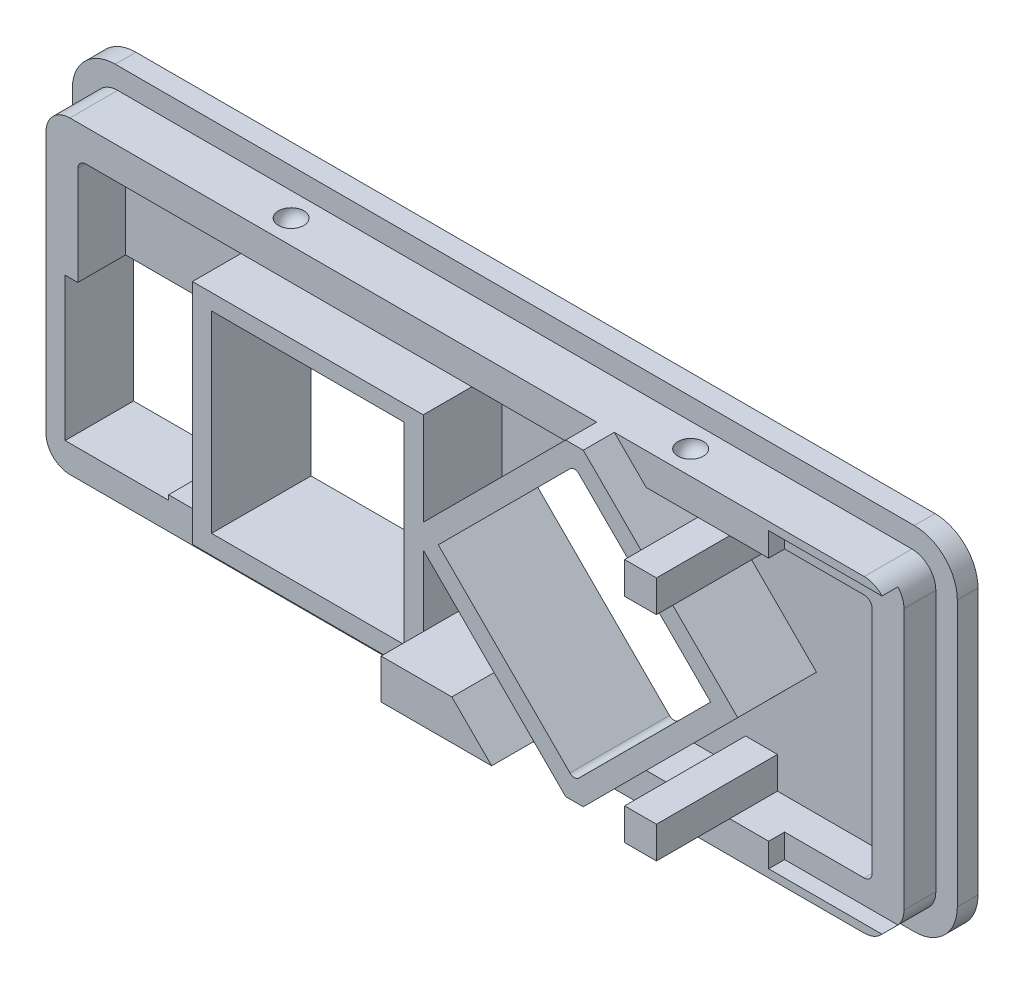
SolidWorks part; units mm, degrees
material "PLA"
ref_plane "Front Plane" through (0, 0, 0) normal (0, 0, 1) x (1, 0, 0)
ref_plane "Top Plane" through (0, 0, 0) normal (0, 1, 0) x (1, 0, 0)
ref_plane "Right Plane" through (0, 0, 0) normal (1, 0, 0) x (0, 0, -1)
sketch "Sketch1" plane through (0, 0, 0) normal (0, 0, 1) x (1, 0, 0)
  line L1 (2.7, 0) -> (52.9, 0)
  line L2 (0, 2.7) -> (0, 19.4)
  line L3 (2.7, 22.1) -> (52.9, 22.1)
  line L4 (55.6, 2.7) -> (55.6, 19.4)
  arc A0 (52.9, 0) -> (55.6, 2.7) centre (52.9, 2.7) ccw
  arc A1 (2.7, 0) -> (0, 2.7) centre (2.7, 2.7) cw
  arc A2 (0, 19.4) -> (2.7, 22.1) centre (2.7, 19.4) cw
  arc A3 (52.9, 22.1) -> (55.6, 19.4) centre (52.9, 19.4) cw
  point P9 (0, 0)
  dimension "D1" = 2.7
  dimension "D2" = 50.2
  dimension "D3" = 22.1
extrude "Boss-Extrude1" add sketch "Sketch1" along normal blind 1.3
sketch "Sketch4" plane through (0, 0, 1.3) normal (0, 0, 1) x (1, 0, 0)
  line L11 (54.25, 2.7) -> (54.25, 19.4)
  line L12 (52.9, 20.75) -> (2.7, 20.75)
  line L13 (1.35, 19.4) -> (1.35, 2.7)
  line L14 (2.7, 1.35) -> (52.9, 1.35)
  line L15 (54.25, 2.85) -> (54.25, 19.25)
  line L16 (52.75, 20.75) -> (2.85, 20.75)
  line L17 (1.35, 19.25) -> (1.35, 2.85)
  line L18 (2.85, 1.35) -> (52.75, 1.35)
  arc A4 (54.25, 19.25) -> (52.75, 20.75) centre (52.75, 19.25) ccw
  arc A5 (54.25, 2.85) -> (52.75, 1.35) centre (52.75, 2.85) cw
  arc A6 (1.35, 2.85) -> (2.85, 1.35) centre (2.85, 2.85) ccw
  arc A7 (2.85, 20.75) -> (1.35, 19.25) centre (2.85, 19.25) ccw
  arc A8 (52.9, 1.35) -> (54.25, 2.7) centre (52.9, 2.7) ccw
  arc A10 (54.25, 19.4) -> (52.9, 20.75) centre (52.9, 19.4) ccw
  arc A12 (2.7, 20.75) -> (1.35, 19.4) centre (2.7, 19.4) ccw
  arc A14 (1.35, 2.7) -> (2.7, 1.35) centre (2.7, 2.7) ccw
  dimension "D2" = 1.5
  dimension "D1" = 1.35
extrude "Boss-Extrude3" add sketch "Sketch4" along normal blind 3
sketch "Sketch5" plane through (0, 0, 4.3) normal (0, 0, 1) x (1, 0, 0)
  line L8 (52.25, 18.75) -> (3.35, 18.75)
  line L9 (3.35, 18.75) -> (3.35, 3.35)
  line L10 (3.35, 3.35) -> (52.25, 3.35)
  line L11 (52.25, 3.35) -> (52.25, 18.75)
  line L12 (51.75, 18.75) -> (3.85, 18.75)
  line L13 (3.35, 18.25) -> (3.35, 3.85)
  line L14 (3.85, 3.35) -> (51.75, 3.35)
  line L15 (52.25, 3.85) -> (52.25, 18.25)
  arc A4 (51.75, 3.35) -> (52.25, 3.85) centre (51.75, 3.85) ccw
  arc A5 (51.75, 18.75) -> (52.25, 18.25) centre (51.75, 18.25) cw
  arc A6 (3.85, 18.75) -> (3.35, 18.25) centre (3.85, 18.25) ccw
  arc A7 (3.35, 3.85) -> (3.85, 3.35) centre (3.85, 3.85) ccw
  dimension "D2" = 0.5
  dimension "D1" = 2
extrude "Cut-Extrude1" cut sketch "Sketch5" against normal blind 3
sketch "Sketch10" plane through (0, 20.75, 0) normal (0, 1, 0) x (1, 0, 0)
  line L0 (40.35, -2) -> (40.35, -3.6)
  line L1 (40.35, -3.6) -> (41.3213, -3.8888)
  line L2 (54.25, -4.3) -> (54.25, -1.3) construction
  line L3 (52.75, -1.3) -> (2.85, -1.3) construction
  arc A0 (40.35, -2) -> (40.35, -3.6) centre (40.35, -2.8) ccw
  dimension "D2" = 0.8
  dimension "D1" = 1.6
  dimension "D3" = 1.5
  dimension "D4" = 13.9
revolve "Cut-Revolve1" cut sketch "Sketch10" angle 360 about L0
ref_plane "Plane1" through (0, 11.05, 0) normal (0, -1, 0) x (-1, 0, 0)
mirror "Mirror1" about plane through (0, 11.05, 0) normal (0, -1, 0) of "Cut-Revolve1"
sketch "Sketch11" plane through (0, 0, 0) normal (0, 0, -1) x (-1, 0, 0)
  line L0 (0, 19.4) -> (0, 2.7) construction
  line L1 (-2.55, 3.05) -> (-9.05, 3.05)
  line L2 (-2.55, 3.05) -> (-2.55, 12.05)
  line L3 (-2.55, 12.05) -> (-9.05, 12.05)
  line L4 (-9.05, 3.05) -> (-9.05, 12.05)
  line L5 (-2.55, 3.05) -> (-9.05, 12.05) construction
  line L6 (-2.55, 12.05) -> (-9.05, 3.05) construction
  line L8 (-2.7, 0) -> (-52.9, 0) construction
  point P0 (-5.8, 7.55)
  dimension "D1" = 5.8
  dimension "D2" = 3.05
  dimension "D3" = 9
  dimension "D4" = 6.5
extrude "Cut-Extrude2" cut sketch "Sketch11" against normal blind 4.3
sketch "Sketch12" plane through (0, 0, 0) normal (0, 0, -1) x (-1, 0, 0)
  line L1 (-25.8, 16.65) -> (-13.7, 16.65)
  line L2 (-25.8, 16.65) -> (-25.8, 4.55)
  line L3 (-25.8, 4.55) -> (-13.7, 4.55)
  line L4 (-13.7, 16.65) -> (-13.7, 4.55)
  line L5 (-25.8, 16.65) -> (-13.7, 4.55) construction
  line L6 (-25.8, 4.55) -> (-13.7, 16.65) construction
  line L7 (-52.9, 22.1) -> (-2.7, 22.1) construction
  line L9 (0, 19.4) -> (0, 2.7) construction
  point P0 (-19.75, 10.6)
  dimension "D1" = 11.5
  dimension "D2" = 19.75
  dimension "D3" = 12.1
  dimension "D4" = 12.1
sketch "Sketch13" plane through (0, 0, 0) normal (0, 0, -1) x (-1, 0, 0)
  line L0 (-45.056, 11.05) -> (-36.5, 2.494)
  line L1 (-45.056, 11.05) -> (-36.5, 19.606)
  line L2 (-36.5, 2.494) -> (-27.944, 11.05)
  line L3 (-36.5, 19.606) -> (-27.944, 11.05)
  line L4 (-45.056, 11.05) -> (-27.944, 11.05) construction
  line L5 (-36.5, 2.494) -> (-36.5, 19.606) construction
  line L6 (-0.715, 11.05) -> (0.715, 11.05) construction
  line L7 (-52.9, 22.1) -> (-2.7, 22.1) construction
  line L10 (0, 19.4) -> (0, 2.7) construction
  point P1 (-36.5, 11.05)
  dimension "D1" = 0
  dimension "D2" = 11.05
  dimension "D3" = 12.1
  dimension "D5" = 36.5
extrude "Cut-Extrude4" cut sketch "Sketch12" against normal blind 1.3
sketch "Sketch17" plane through (0, 0, 0) normal (0, 0, -1) x (-1, 0, 0)
  line L8 (-13.7, 16.65) -> (-25.8, 16.65) construction
  line L9 (-27, 17.65) -> (-12.5, 17.65)
  line L10 (-27, 17.65) -> (-27, 3.35)
  line L11 (-27, 3.35) -> (-12.5, 3.35)
  line L12 (-12.5, 17.65) -> (-12.5, 3.35)
  line L13 (-25.8, 4.55) -> (-13.7, 4.55) construction
  line L14 (-13.7, 4.55) -> (-13.7, 16.65) construction
  line L15 (-25.8, 16.65) -> (-25.8, 4.55) construction
  line L17 (-13.7, 4.55) -> (-25.8, 4.55)
  line L18 (-13.7, 4.55) -> (-13.7, 16.65)
  line L19 (-13.7, 16.65) -> (-25.8, 16.65)
  line L20 (-25.8, 4.55) -> (-25.8, 16.65)
  dimension "D1" = 1
  dimension "D2" = 1.2
  dimension "D3" = 1.2
  dimension "D4" = 1.2
extrude "Boss-Extrude4" add sketch "Sketch17" against normal blind 6.25
extrude "Cut-Extrude5" cut sketch "Sketch13" against normal blind 4.3
sketch "Sketch18" plane through (0, 0, 0) normal (0, 0, -1) x (-1, 0, 0)
  line L18 (-36.5, 19.606) -> (-45.056, 11.05)
  line L19 (-45.056, 11.05) -> (-36.5, 2.494)
  line L20 (-36.5, 2.494) -> (-27.944, 11.05)
  line L21 (-27.944, 11.05) -> (-36.5, 19.606)
  line L22 (-46.753, 11.05) -> (-36.5, 0.797)
  line L23 (-36.5, 0.797) -> (-26.247, 11.05)
  line L24 (-26.247, 11.05) -> (-36.5, 21.303)
  line L25 (-36.5, 21.303) -> (-46.753, 11.05)
  line L26 (-46.753, 11.05) -> (-36.5, 0.797)
  line L27 (-36.5, 0.797) -> (-26.247, 11.05)
  line L28 (-26.247, 11.05) -> (-36.5, 21.303)
  line L29 (-36.5, 21.303) -> (-46.753, 11.05)
  dimension "D1" = 1.2
extrude "Boss-Extrude5" add sketch "Sketch18" against normal blind 6.25
sketch "Sketch20" plane through (0, 0, 4.3) normal (0, 0, 1) x (1, 0, 0)
  line L0 (35.947, 20.75) -> (37.053, 20.75)
  line L1 (35.947, 20.75) -> (2.85, 20.75) construction
  line L2 (52.75, 20.75) -> (37.053, 20.75) construction
  line L3 (37.053, 20.75) -> (36.5, 21.303)
  line L4 (36.5, 21.303) -> (35.947, 20.75)
extrude "Cut-Extrude6" cut sketch "Sketch20" against normal blind 3 and the other way blind 20
mirror "Mirror2" about plane through (0, 11.05, 0) normal (0, -1, 0) of "Cut-Extrude6"
sketch "Sketch21" plane through (0, 0, 0) normal (0, 0, -1) x (-1, 0, 0)
  line L0 (-52.9, 22.1) -> (-2.7, 22.1) construction
  line L1 (-30.25, 18.35) -> (-27.75, 18.35)
  line L2 (-30.25, 18.35) -> (-30.25, 15.85)
  line L3 (-30.25, 15.85) -> (-27.75, 15.85)
  line L4 (-27.75, 18.35) -> (-27.75, 15.85)
  line L5 (-30.25, 18.35) -> (-27.75, 15.85) construction
  line L6 (-30.25, 15.85) -> (-27.75, 18.35) construction
  line L7 (0, 19.4) -> (0, 2.7) construction
  point P0 (-29, 17.1)
  dimension "D1" = 5
  dimension "D2" = 2.5
  dimension "D3" = 2.5
  dimension "D4" = 29
extrude "Cut-Extrude7" cut sketch "Sketch21" against normal blind 10
ref_plane "Plane2" through (27.8, 0, 0) normal (-1, 0, 0) x (0, 0, 1)
mirror "Mirror3" about plane through (27.8, 0, 0) normal (-1, 0, 0) of "Mirror1", "Cut-Revolve1"
sketch "Sketch24" plane through (0, 0, 1.3) normal (0, 0, 1) x (1, 0, 0)
  line L0 (33.947, 3.35) -> (27, 3.35)
  line L2 (27, 3.35) -> (27, 5.85)
  line L3 (27, 3.35) -> (33.947, 3.35) construction
  line L4 (27, 5.85) -> (31.447, 5.85)
  line L5 (27, 10.297) -> (33.947, 3.35) construction
  line L6 (31.447, 5.85) -> (33.947, 3.35)
  line L8 (27, 11.803) -> (27, 17.65) construction
  dimension "D1" = 2.5
extrude "Boss-Extrude7" add sketch "Sketch24" along normal blind 7.6
sketch "Sketch25" plane through (0, 0, 1.3) normal (0, 0, 1) x (1, 0, 0)
  line L1 (44.3, 3.35) -> (42.3, 3.35)
  line L2 (44.3, 3.35) -> (44.3, 5.35)
  line L3 (44.3, 5.35) -> (42.3, 5.35)
  line L4 (42.3, 3.35) -> (42.3, 5.35)
  line L5 (55.6, 2.7) -> (55.6, 19.4) construction
  line L8 (39.053, 3.35) -> (51.75, 3.35) construction
  dimension "D1" = 11.3
  dimension "D2" = 2
  dimension "D3" = 2
extrude "Boss-Extrude8" add sketch "Sketch25" along normal blind 7.6
mirror "Mirror4" about plane through (0, 11.05, 0) normal (0, -1, 0) of "Boss-Extrude8"
sketch "Sketch23" plane through (0, 0, 1.3) normal (0, 0, 1) x (1, 0, 0)
  line L0 (-0.715, 11.05) -> (0.715, 11.05) construction
  line L1 (48.7, 3.35) -> (46.3, 3.35)
  line L2 (48.7, 3.35) -> (48.7, 18.75)
  line L3 (48.7, 18.75) -> (46.3, 18.75)
  line L4 (46.3, 3.35) -> (46.3, 18.75)
  line L5 (48.7, 3.35) -> (46.3, 18.75) construction
  line L6 (48.7, 18.75) -> (46.3, 3.35) construction
  line L7 (39.053, 3.35) -> (42.3, 3.35) construction
  line L8 (51.75, 18.75) -> (44.3, 18.75) construction
  line L9 (0, 19.4) -> (0, 2.7) construction
  point P0 (47.5, 11.05)
  dimension "D1" = 2.4
  dimension "D2" = 47.5
extrude "Boss-Extrude6" [suppressed] add sketch "Sketch23" along normal blind 3
sketch "Sketch27" plane through (54.25, 0, 0) normal (1, 0, 0) x (0, 0, -1)
  line L0 (-4.3, 2.85) -> (-4.3, 19.25) construction
  line L2 (-3.3, 20.25) -> (-4.3, 20.25)
  line L3 (-3.3, 20.25) -> (-3.3, 1.85)
  line L4 (-3.3, 1.85) -> (-4.3, 1.85)
  line L5 (-4.3, 20.25) -> (-4.3, 1.85)
  line L6 (-3.3, 20.25) -> (-4.3, 1.85) construction
  line L7 (-3.3, 1.85) -> (-4.3, 20.25) construction
  point P2 (-4.3, 11.05)
  point P3 (-3.8, 11.05)
  dimension "D1" = 1
  dimension "D2" = 18.4
extrude "Cut-Extrude8" cut sketch "Sketch27" against normal blind 7.5
fillet "Fillet1" radius 0.4 2 edges at (36.5, 19.606, 3.125) (36.5, 2.494, 3.125)
equation "\"OutterLength\"= 55.6mm"
equation "\"OutterWidth\"= 21.1mm"
equation "\"EdgeRadius\"= 2.7mm"
equation "\"LipOffset\"= 1.35mm"
equation "\"LipHeight\"= 3mm"
equation "\"LipThickness\"= 2mm"
equation "\"LatchRadius\"= 0.8mm"
equation "\"D2@Sketch1\"=\"OutterLength\"-\"EdgeRadius\"*2"
equation "\"D1@Sketch1\"=\"EdgeRadius\""
equation "\"D1@Sketch4\"=\"LipOffset\""
equation "\"LipRadius\"= 1.5mm"
equation "\"D2@Sketch4\"=\"LipRadius\""
equation "\"D1@Sketch5\"=\"LipThickness\""
equation "\"D1@Boss-Extrude3\"=\"LipHeight\""
equation "\"D1@Cut-Extrude1\"=\"LipHeight\""
equation "\"D2@Sketch10\"=\"LatchRadius\""
equation "\"D1@Sketch10\"=\"LatchRadius\"*2"
equation "\"D3@Sketch10\"=\"LipHeight\"/2"
equation "\"D1@Cut-Extrude2\"=\"LipHeight\"+\"WallThickness\""
equation "\"WallThickness\"= 1.3mm"
equation "\"D1@Boss-Extrude1\"=\"WallThickness\""
equation "\"D1@Cut-Extrude4\"=\"WallThickness\""
equation "\"D1@Cut-Extrude5\"=\"WallThickness\"+\"LipHeight\""
equation "\"D1@Cut-Extrude6\"=\"LipHeight\""
equation "\"D2@Cut-Extrude6\"=20mm"
